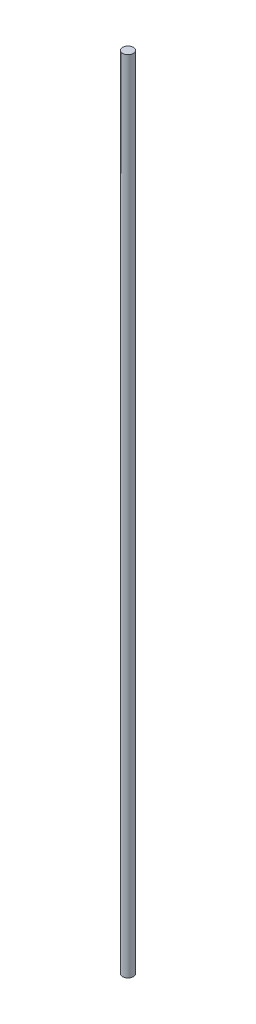
SolidWorks part; units mm, degrees
ref_plane "Plan de face" through (0, 0, 0) normal (0, 0, 1) x (1, 0, 0)
ref_plane "Plan de dessus" through (0, 0, 0) normal (0, 1, 0) x (1, 0, 0)
ref_plane "Plan de droite" through (0, 0, 0) normal (1, 0, 0) x (0, 0, -1)
sketch "Esquisse1" plane through (0, 0, 0) normal (0, 1, 0) x (1, 0, 0)
  circle A0 centre (-18.939, 21.6065) radius 1
  dimension "D1" = 2
extrude "Boss.-Extru.1" add sketch "Esquisse1" along normal blind 150
